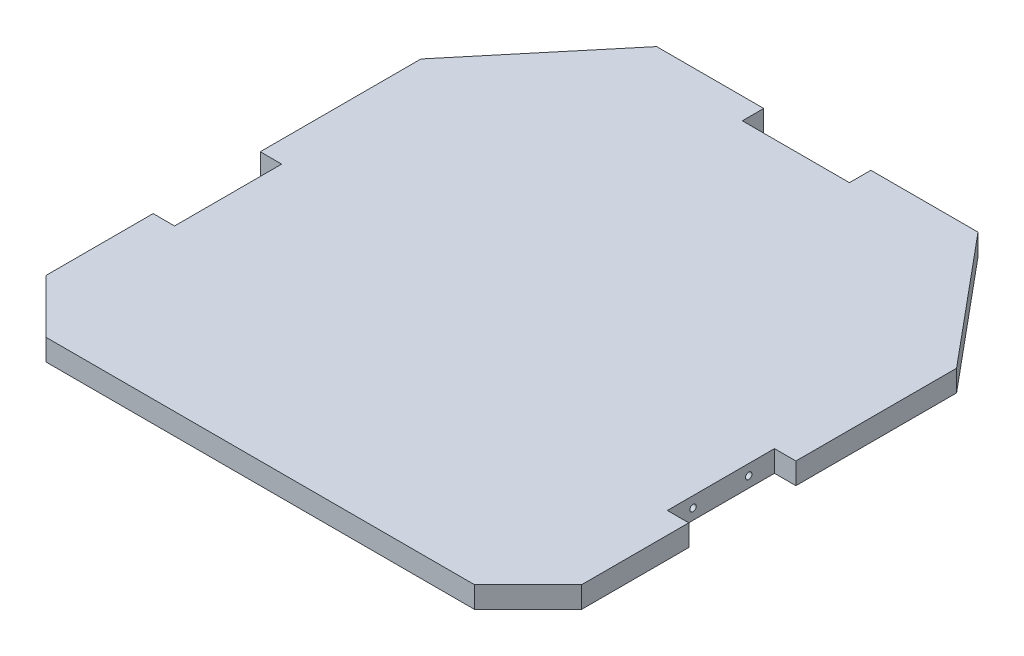
SolidWorks part; units mm, degrees
material "ABS PC"
ref_plane "Спереди" through (0, 0, 0) normal (0, 0, 1) x (1, 0, 0)
ref_plane "Сверху" through (0, 0, 0) normal (0, 1, 0) x (1, 0, 0)
ref_plane "Справа" through (0, 0, 0) normal (1, 0, 0) x (0, 0, -1)
sketch "Sketch1" plane through (0, 0, 0) normal (0, 1, 0) x (1, 0, 0)
  line L0 (-125, 200) -> (-125, 125)
  line L1 (-125, 200) -> (-75, 260)
  line L2 (-75, 260) -> (-25, 260)
  line L3 (0, 260) -> (0, 0) construction
  line L4 (-25, 260) -> (-25, 250)
  line L6 (-25, 250) -> (25, 250)
  line L7 (-125, 125) -> (-115, 125)
  line L8 (-115, 125) -> (-115, 75)
  line L9 (-115, 75) -> (-125, 75)
  line L10 (-125, 75) -> (-125, 25)
  line L11 (-25, 260) -> (25, 260) construction
  line L12 (-125, 125) -> (-125, 75) construction
  line L13 (125, 260) -> (75, 260) construction
  line L14 (125, 200) -> (125, 260) construction
  line L15 (125, 125) -> (125, 75) construction
  line L16 (-100, 0) -> (100, 0)
  line L17 (125, 0) -> (100, 0) construction
  line L18 (-125, 200) -> (-125, 260) construction
  line L19 (-125, 260) -> (-75, 260) construction
  line L20 (115, 75) -> (125, 75)
  line L21 (115, 125) -> (115, 75)
  line L22 (125, 125) -> (115, 125)
  line L23 (125, 25) -> (125, 0) construction
  line L24 (25, 260) -> (25, 250)
  line L25 (75, 260) -> (25, 260)
  line L26 (125, 200) -> (75, 260)
  line L27 (125, 200) -> (125, 125)
  line L28 (-125, 25) -> (-100, 0)
  line L29 (-125, 25) -> (-125, 0) construction
  line L30 (-125, 0) -> (-100, 0) construction
  line L31 (125, 25) -> (100, 0)
  line L32 (125, 75) -> (125, 25)
  point P25 (0, 250)
  dimension "D2" = 125
  dimension "D3" = 60
  dimension "D4" = 50
  dimension "D5" = 50
  dimension "D6" = 25
  dimension "D7" = 75
  dimension "D8" = 10
  dimension "D9" = 25
  dimension "D10" = 25
  dimension "D11" = 260
extrude "Boss-Extrude1" add sketch "Sketch1" along normal blind 10
sketch "Sketch2" plane through (-115, 0, 0) normal (-1, 0, 0) x (0, 0, 1)
  line L0 (-125, 10) -> (-125, 0) construction
  line L1 (-75, 10) -> (-75, 0) construction
  line L2 (-125, 10) -> (-75, 10) construction
  circle A0 centre (-113, 5) radius 1.5
  circle A1 centre (-87, 5) radius 1.5
  point P6 (-75, 5)
  dimension "D1" = 3
  dimension "D2" = 12
  dimension "D3" = 12
  dimension "D4" = 5
extrude "Cut-Extrude1" cut sketch "Sketch2" against normal blind 15
mirror "Mirror1" about plane through (0, 0, 0) normal (1, 0, 0) of "Cut-Extrude1"
sketch "Sketch3" plane through (0, 0, -250) normal (0, 0, -1) x (-1, 0, 0)
  line L0 (-25, 10) -> (-25, 0) construction
  line L1 (25, 10) -> (25, 0) construction
  line L2 (25, 10) -> (-25, 10) construction
  circle A0 centre (-13, 5) radius 1.5
  circle A1 centre (13, 5) radius 1.5
  dimension "D1" = 3
  dimension "D2" = 12
  dimension "D3" = 12
  dimension "D4" = 5
extrude "Cut-Extrude2" cut sketch "Sketch3" against normal blind 15
